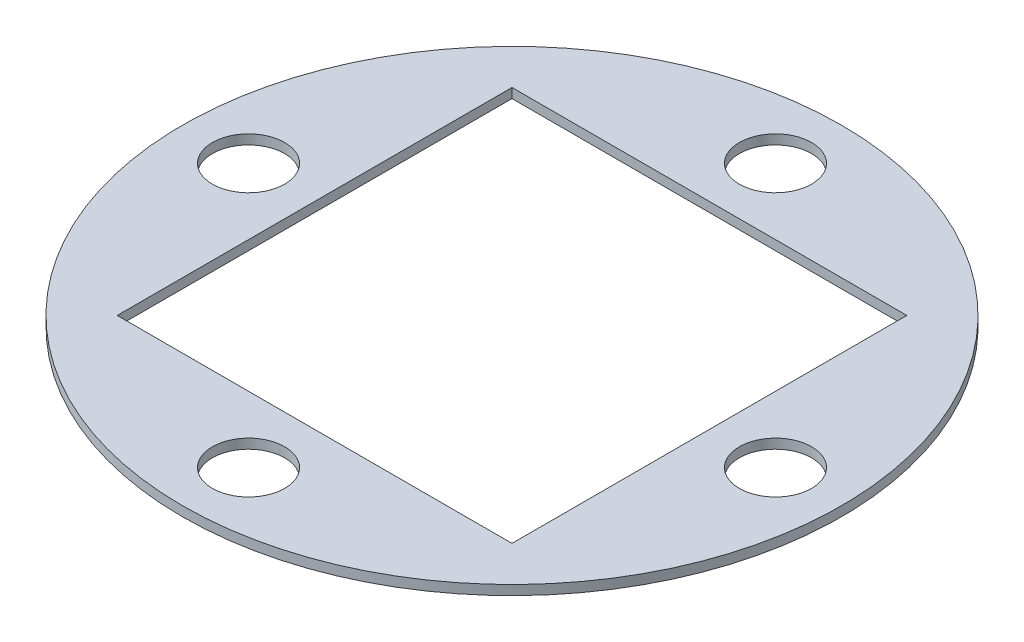
SolidWorks part; units mm, degrees
ref_plane "Front Plane" through (0, 0, 0) normal (0, 0, 1) x (1, 0, 0)
ref_plane "Top Plane" through (0, 0, 0) normal (0, 1, 0) x (1, 0, 0)
ref_plane "Right Plane" through (0, 0, 0) normal (1, 0, 0) x (0, 0, -1)
sketch "Sketch1" plane through (0, 0, 0) normal (0, 1, 0) x (1, 0, 0)
  circle A0 centre (0, 0) radius 86.9315
extrude "Boss-Extrude1" add sketch "Sketch1" along normal blind 2.54
sketch "Sketch2" plane through (0, 2.54, 0) normal (0, 1, 0) x (1, 0, 0)
  line L1 (-52.07, 52.07) -> (52.07, 52.07)
  line L2 (-52.07, 52.07) -> (-52.07, -52.07)
  line L3 (-52.07, -52.07) -> (52.07, -52.07)
  line L4 (52.07, 52.07) -> (52.07, -52.07)
  line L5 (-52.07, 52.07) -> (52.07, -52.07) construction
  line L6 (-52.07, -52.07) -> (52.07, 52.07) construction
  point P0 (0, 0)
extrude "Cut-Extrude1" cut sketch "Sketch2" against normal blind 2.54
sketch "Sketch3" plane through (0, 2.54, 0) normal (0, 1, 0) x (1, 0, 0)
  line L0 (0, 86.9315) -> (0, 52.07) construction
  line L1 (-86.9315, 0) -> (-52.07, 0) construction
  line L2 (0, -52.07) -> (0, -86.9315) construction
  line L3 (-52.07, -52.07) -> (52.07, -52.07)
  line L4 (-52.07, -52.07) -> (-52.07, 52.07)
  line L5 (-52.07, 52.07) -> (52.07, 52.07)
  line L6 (52.07, -52.07) -> (52.07, 52.07)
  line L9 (52.07, 0) -> (86.9315, 0) construction
  circle A0 centre (0, 69.5007) radius 9.525
  circle A2 centre (69.5007, 0) radius 9.525
  circle A4 centre (0, -69.5007) radius 9.525
  circle A5 centre (-69.5007, 0) radius 9.525
  point P0 (0, 0)
extrude "Cut-Extrude3" cut sketch "Sketch3" against normal blind 203.2 contours L4 L3 L6 L5 | A0 | A2 | A4 | A5
